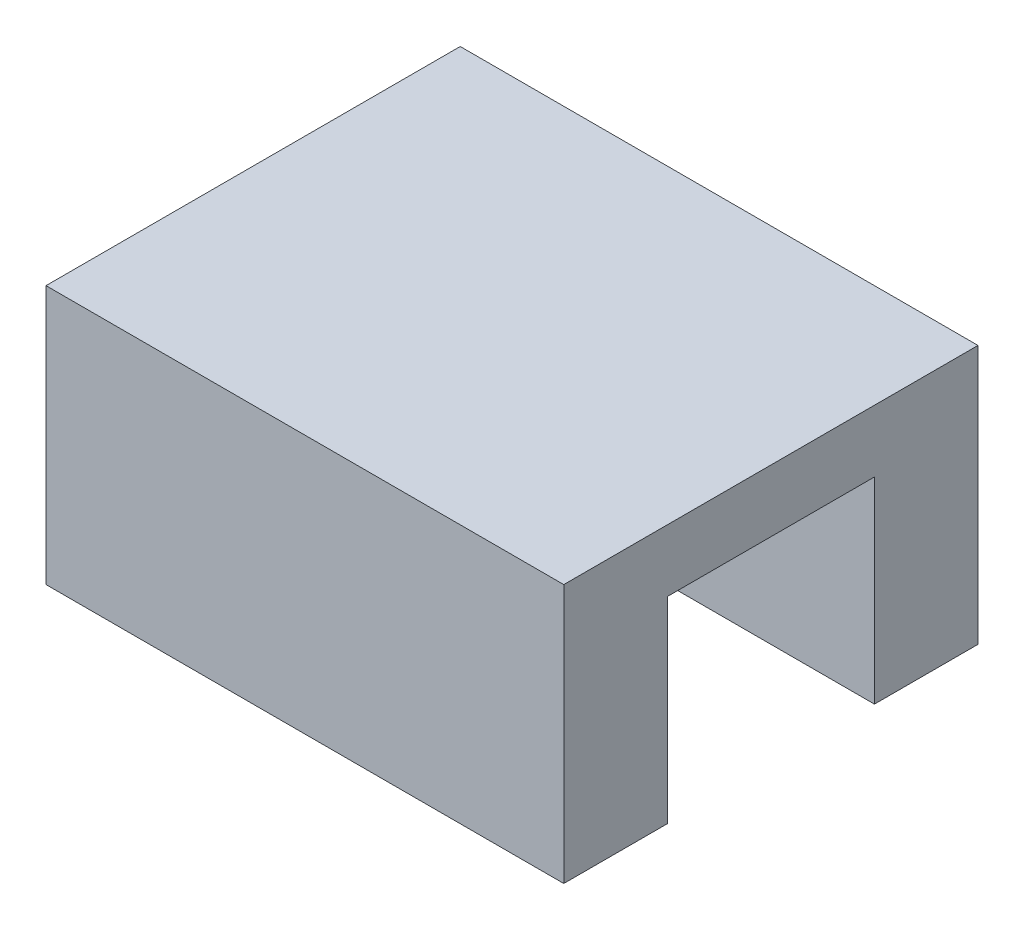
SolidWorks part; units mm, degrees
ref_plane "Plano frontal" through (0, 0, 0) normal (0, 0, 1) x (1, 0, 0)
ref_plane "Plano superior" through (0, 0, 0) normal (0, 1, 0) x (1, 0, 0)
ref_plane "Plano direito" through (0, 0, 0) normal (1, 0, 0) x (0, 0, -1)
sketch "Esboço1" plane through (0, 0, 0) normal (0, 0, 1) x (1, 0, 0)
  line L0 (0, 0) -> (50, 0)
  line L1 (0, 0) -> (0, 25)
  line L2 (50, 0) -> (50, 25)
  line L3 (50, 25) -> (0, 25)
  dimension "D1" = 50
  dimension "D2" = 25
extrude "Ressalto-extrusão1" add sketch "Esboço1" along normal blind 10
sketch "Esboço2" plane through (0, 25, 0) normal (0, 1, 0) x (1, 0, 0)
  line L0 (0, 0) -> (50, 0)
  line L1 (50, 0) -> (50, 20)
  line L2 (50, 20) -> (0, 20)
  line L3 (0, 20) -> (0, 0)
  dimension "D1" = 20
extrude "Ressalto-extrusão2" add sketch "Esboço2" against normal blind 6 contours L3 L0 L1 L2
sketch "Esboço3" plane through (0, 0, -20) normal (0, 0, -1) x (-1, 0, 0)
  line L0 (0, 25) -> (0, 0)
  line L1 (0, 25) -> (-50, 25)
  line L2 (-50, 25) -> (-50, 0)
  line L3 (-50, 0) -> (0, 0)
extrude "Ressalto-extrusão3" add sketch "Esboço3" along normal blind 10
